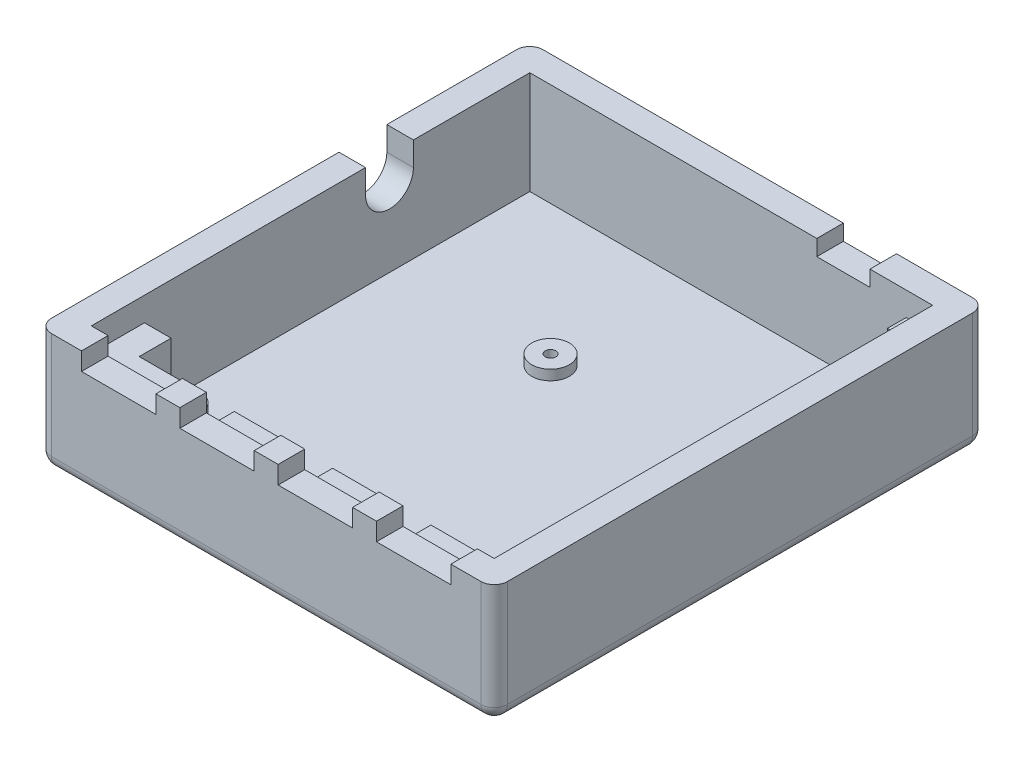
SolidWorks part; units mm, degrees
ref_plane "Front Plane" through (0, 0, 0) normal (0, 0, 1) x (1, 0, 0)
ref_plane "Top Plane" through (0, 0, 0) normal (0, 1, 0) x (1, 0, 0)
ref_plane "Right Plane" through (0, 0, 0) normal (1, 0, 0) x (0, 0, -1)
sketch "Sketch1" plane through (0, 0, 0) normal (0, 1, 0) x (1, 0, 0)
  line L0 (5, 4) -> (5, 10)
  line L1 (5, 10) -> (0, 10)
  line L2 (0, 10) -> (0, 82.5)
  line L3 (0, 82.5) -> (70.8, 82.5)
  line L4 (70.8, 82.5) -> (70.8, 79)
  line L5 (70.8, 79) -> (75.8, 79)
  line L6 (75.8, 79) -> (75.8, 4)
  line L7 (5, 4) -> (15.9, 4)
  line L8 (15.9, 4) -> (15.9, 0)
  line L9 (15.9, 0) -> (22.9, 0)
  line L10 (22.9, 0) -> (22.9, 4)
  line L11 (22.9, 4) -> (34.4, 4)
  line L12 (34.4, 4) -> (34.4, 0)
  line L13 (34.4, 0) -> (41.4, 0)
  line L14 (41.4, 0) -> (41.4, 4)
  line L15 (41.4, 4) -> (52.9, 4)
  line L16 (52.9, 4) -> (52.9, 0)
  line L17 (52.9, 0) -> (59.9, 0)
  line L18 (59.9, 0) -> (59.9, 4)
  line L19 (59.9, 4) -> (75.8, 4)
  line L20 (19.4, 27.0002) -> (19.4, -18.5168) construction
  line L21 (37.9, 24.8892) -> (37.9, -19.4403) construction
  line L22 (56.4, 24.8892) -> (56.4, -19.4529) construction
  line L23 (-5, 87.5) -> (-5, -5)
  line L24 (-5, -5) -> (80.8, -5)
  line L25 (80.8, -5) -> (80.8, 87.5)
  line L26 (80.8, 87.5) -> (-5, 87.5)
  dimension "D1" = 82.5
  dimension "D2" = 75.8
  dimension "D3" = 3.5
  dimension "D4" = 5
  dimension "D5" = 7
  dimension "D6" = 7
  dimension "D7" = 7
  dimension "D8" = 19.4
  dimension "D9" = 18.5
  dimension "D10" = 18.5
  dimension "D11" = 5
  dimension "D12" = 4
  dimension "D13" = 6
  dimension "D14" = 5
  dimension "D15" = 5
  dimension "D16" = 5
  dimension "D17" = 5
extrude "Boss-Extrude1" add sketch "Sketch1" along normal blind 14.859
sketch "Sketch2" plane through (0, 0, 0) normal (0, 1, 0) x (1, 0, 0)
  line L0 (-5, 87.5) -> (-5, -5) construction
  line L1 (-5, 87.5) -> (80.8, 87.5)
  line L2 (-5, 87.5) -> (-5, -5)
  line L3 (-5, -5) -> (80.8, -5)
  line L4 (80.8, 87.5) -> (80.8, -5)
  line L5 (80.8, 87.5) -> (-5, 87.5) construction
  line L6 (80.8, -5) -> (80.8, 87.5) construction
  line L7 (-5, -5) -> (80.8, -5) construction
  circle A0 centre (3.5, 13.5) radius 1
  circle A1 centre (19.4, 3.5) radius 1
  circle A2 centre (37.9, 3.5) radius 1
  circle A3 centre (56.4, 3.5) radius 1
  circle A4 centre (30.3, 56.1) radius 1
  circle A5 centre (71.8, 75.5) radius 1
  dimension "D3" = 2
  dimension "D1" = 3.5
  dimension "D2" = 13.5
  dimension "D4" = 19.4
  dimension "D5" = 18.5
  dimension "D6" = 18.5
  dimension "D7" = 3.5
  dimension "D8" = 56.1
  dimension "D9" = 30.3
  dimension "D10" = 71.8
  dimension "D11" = 75.5
extrude "Boss-Extrude2" add sketch "Sketch2" against normal blind 3.175
ref_plane "Plane1" through (0, 14.859, 0) normal (0, 1, 0) x (1, 0, 0)
sketch "Sketch4" plane through (0, 14.859, 0) normal (0, 1, 0) x (1, 0, 0)
  line L1 (0, 0) -> (75.8, 0)
  line L2 (0, 0) -> (0, 82.5)
  line L3 (0, 82.5) -> (75.8, 82.5)
  line L4 (75.8, 0) -> (75.8, 82.5)
  line L5 (-5, -5) -> (80.8, -5)
  line L6 (-5, -5) -> (-5, 87.5)
  line L7 (-5, 87.5) -> (80.8, 87.5)
  line L8 (80.8, -5) -> (80.8, 87.5)
  dimension "D1" = 82.5
  dimension "D2" = 75.8
  dimension "D3" = 5
  dimension "D4" = 5
  dimension "D5" = 5
  dimension "D6" = 5
extrude "Boss-Extrude3" add sketch "Sketch4" along normal blind 4.5
sketch "Sketch3" plane through (0, 0, 0) normal (1, 0, 0) x (0, 0, -1)
  line L0 (60.6, 14.859) -> (60.6, 19.359)
  line L1 (87.5, 19.359) -> (-5, 19.359) construction
  line L2 (51.6, 14.859) -> (51.6, 19.359)
  line L3 (60.6, 19.359) -> (51.6, 19.359)
  circle A0 centre (56.1, 14.859) radius 4.5 construction
  arc A1 (60.6, 14.859) -> (51.6, 14.859) centre (56.1, 14.859) cw
  dimension "D1" = 9
  dimension "D2" = 56.1
  dimension "D3" = 14.859
extrude "Cut-Extrude1" cut sketch "Sketch3" against normal through all
sketch "Sketch5" plane through (0, 0, 0) normal (0, 0, 1) x (1, 0, 0)
  line L1 (3.15, 24) -> (17.15, 24)
  line L2 (3.15, 24) -> (3.15, 16)
  line L3 (3.15, 16) -> (17.15, 16)
  line L4 (17.15, 24) -> (17.15, 16)
  line L5 (21.65, 24) -> (35.65, 24)
  line L6 (21.65, 24) -> (21.65, 16)
  line L7 (21.65, 16) -> (35.65, 16)
  line L8 (35.65, 24) -> (35.65, 16)
  line L9 (40.15, 24) -> (54.15, 24)
  line L10 (40.15, 24) -> (40.15, 16)
  line L11 (40.15, 16) -> (54.15, 16)
  line L12 (54.15, 24) -> (54.15, 16)
  line L13 (72.65, 24) -> (58.65, 24)
  line L14 (72.65, 24) -> (72.65, 16)
  line L15 (72.65, 16) -> (58.65, 16)
  line L16 (58.65, 24) -> (58.65, 16)
  point P16 (10.15, 16)
  point P17 (28.65, 16)
  point P18 (47.15, 16)
  point P19 (65.65, 16)
  dimension "D1" = 10.15
  dimension "D2" = 18.5
  dimension "D3" = 18.5
  dimension "D4" = 18.5
  dimension "D5" = 14
  dimension "D6" = 14
  dimension "D7" = 14
  dimension "D8" = 14
  dimension "D9" = 16
  dimension "D10" = 8
extrude "Cut-Extrude2" cut sketch "Sketch5" along normal through all
sketch "Sketch6" plane through (0, 0, 0) normal (0, 0, 1) x (1, 0, 0)
  line L1 (54, 16.383) -> (64, 16.383)
  line L4 (64, 16.383) -> (64, 22.383)
  line L5 (64, 22.383) -> (54, 22.383)
  line L6 (54, 22.383) -> (54, 16.383)
  point P0 (59, 16.383)
  dimension "D1" = 59
  dimension "D2" = 10
  dimension "D3" = 6
  dimension "D4" = 16.383
extrude "Cut-Extrude3" cut sketch "Sketch6" against normal through all
sketch "Sketch7" plane through (0, 0, 0) normal (0, 1, 0) x (1, 0, 0)
  line L0 (0, 13.5) -> (0, 10)
  line L1 (0, 51.6) -> (0, 0) construction
  line L2 (0, 10) -> (3.5, 10)
  line L3 (0, 10) -> (5, 10) construction
  line L4 (15.9, 3.5) -> (15.9, 0)
  line L5 (15.9, 4) -> (15.9, 0) construction
  line L6 (15.9, 0) -> (22.9, 0)
  line L7 (22.9, 0) -> (22.9, 3.5)
  line L8 (22.9, 0) -> (22.9, 4) construction
  line L9 (34.4, 3.5) -> (34.4, 0)
  line L10 (34.4, 4) -> (34.4, 0) construction
  line L11 (21.65, 0) -> (35.65, 0) construction
  line L12 (22.9, 0) -> (34.4, 0) construction
  line L13 (34.4, 0) -> (41.4, 0)
  line L14 (41.4, 0) -> (41.4, 3.5)
  line L15 (41.4, 0) -> (41.4, 4) construction
  line L16 (52.9, 3.5) -> (52.9, 0)
  line L17 (52.9, 4) -> (52.9, 0) construction
  line L18 (52.9, 0) -> (59.9, 0)
  line L19 (59.9, 0) -> (59.9, 3.5)
  line L20 (59.9, 0) -> (59.9, 4) construction
  line L21 (75.8, 79) -> (69.8635, 79)
  line L22 (75.8, 79) -> (70.8, 79) construction
  line L23 (75.8, 79) -> (75.8, 75.5)
  line L24 (75.8, 0) -> (75.8, 82.5) construction
  circle A0 centre (30.3, 56.1) radius 3.54
  circle A1 centre (30.3, 56.1) radius 1
  circle A2 centre (3.5, 13.5) radius 1
  arc A3 (0, 13.5) -> (3.5, 10) centre (3.5, 13.5) cw
  circle A4 centre (19.4, 3.5) radius 1
  arc A5 (15.9, 3.5) -> (22.9, 3.5) centre (19.4, 3.5) cw
  circle A6 centre (37.9, 3.5) radius 1
  arc A7 (34.4, 3.5) -> (41.4, 3.5) centre (37.9, 3.5) cw
  circle A8 centre (56.4, 3.5) radius 1
  arc A9 (52.9, 3.5) -> (59.9, 3.5) centre (56.4, 3.5) cw
  circle A10 centre (71.8, 75.5) radius 1
  arc A11 (75.8, 75.5) -> (69.8635, 79) centre (71.8, 75.5) cw
  dimension "D1" = 2.54
  dimension "D2" = 2
  dimension "D3" = 2
  dimension "D4" = 2
  dimension "D5" = 2
  dimension "D7" = 2
  dimension "D9" = 2
extrude "Boss-Extrude4" add sketch "Sketch7" along normal blind 1.9
fillet "Fillet1" radius 2.5 1 edges at (-5, 8.092, 5)
fillet "Fillet2" radius 2.5 1 edges at (80.8, 8.092, 5)
fillet "Fillet3" radius 2.5 1 edges at (80.8, 8.092, -87.5)
fillet "Fillet4" radius 2.5 1 edges at (-5, 8.092, -87.5)
fillet "Fillet5" radius 2.5 8 edges at (80.0678, -3.175, 4.2678) (37.9, -3.175, 5) (-4.2678, -3.175, 4.2678) (-5, -3.175, -41.25) (-4.2678, -3.175, -86.7678) (37.9, -3.175, -87.5) (80.0678, -3.175, -86.7678) (80.8, -3.175, -41.25)
